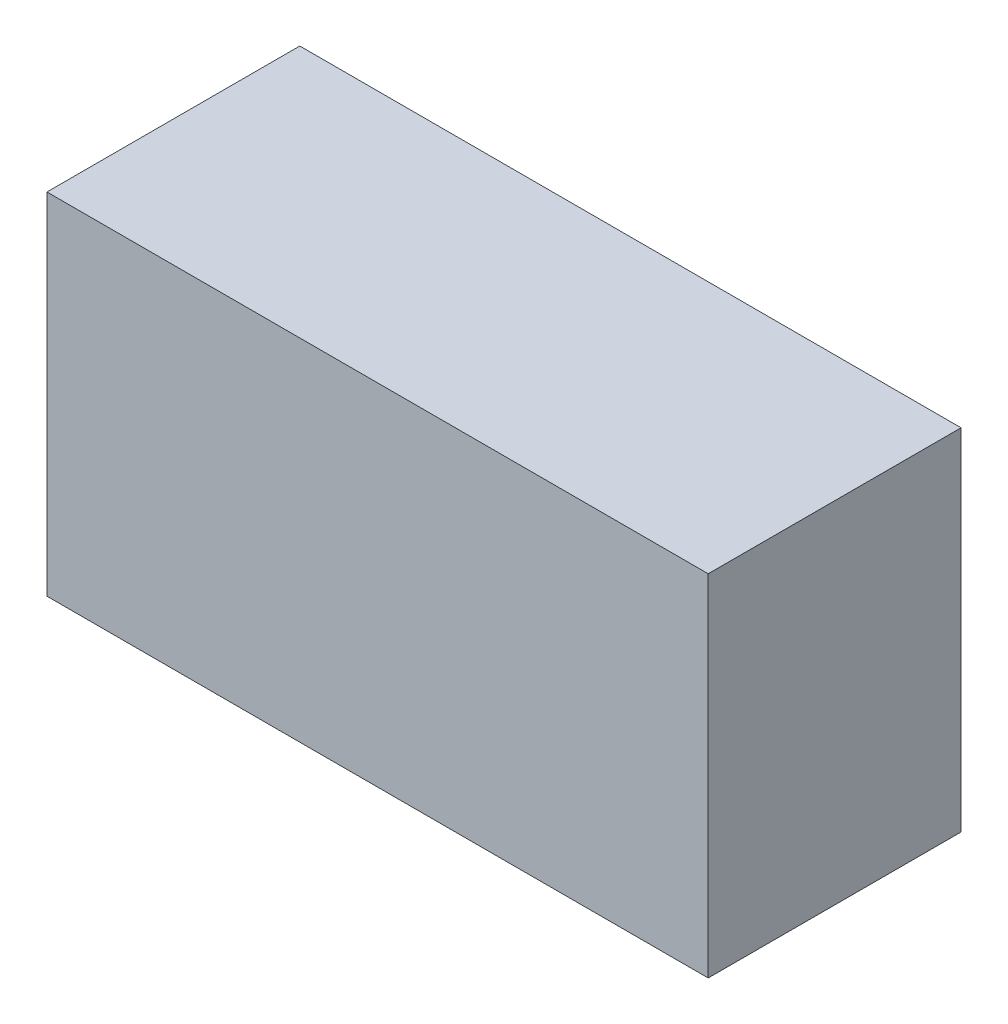
SolidWorks part; units mm, degrees
ref_plane "Front Plane" through (0, 0, 0) normal (0, 0, 1) x (1, 0, 0)
ref_plane "Top Plane" through (0, 0, 0) normal (0, 1, 0) x (1, 0, 0)
ref_plane "Right Plane" through (0, 0, 0) normal (1, 0, 0) x (0, 0, -1)
sketch "Sketch1" plane through (0, 0, 0) normal (0, 0, 1) x (1, 0, 0)
  line L1 (-25.5, -13.5) -> (25.5, -13.5)
  line L2 (-25.5, -13.5) -> (-25.5, 13.5)
  line L3 (-25.5, 13.5) -> (25.5, 13.5)
  line L4 (25.5, -13.5) -> (25.5, 13.5)
  line L5 (-25.5, -13.5) -> (25.5, 13.5) construction
  line L6 (-25.5, 13.5) -> (25.5, -13.5) construction
  point P0 (0, 0)
extrude "Envelope" add sketch "Sketch1" along normal blind 19.5
